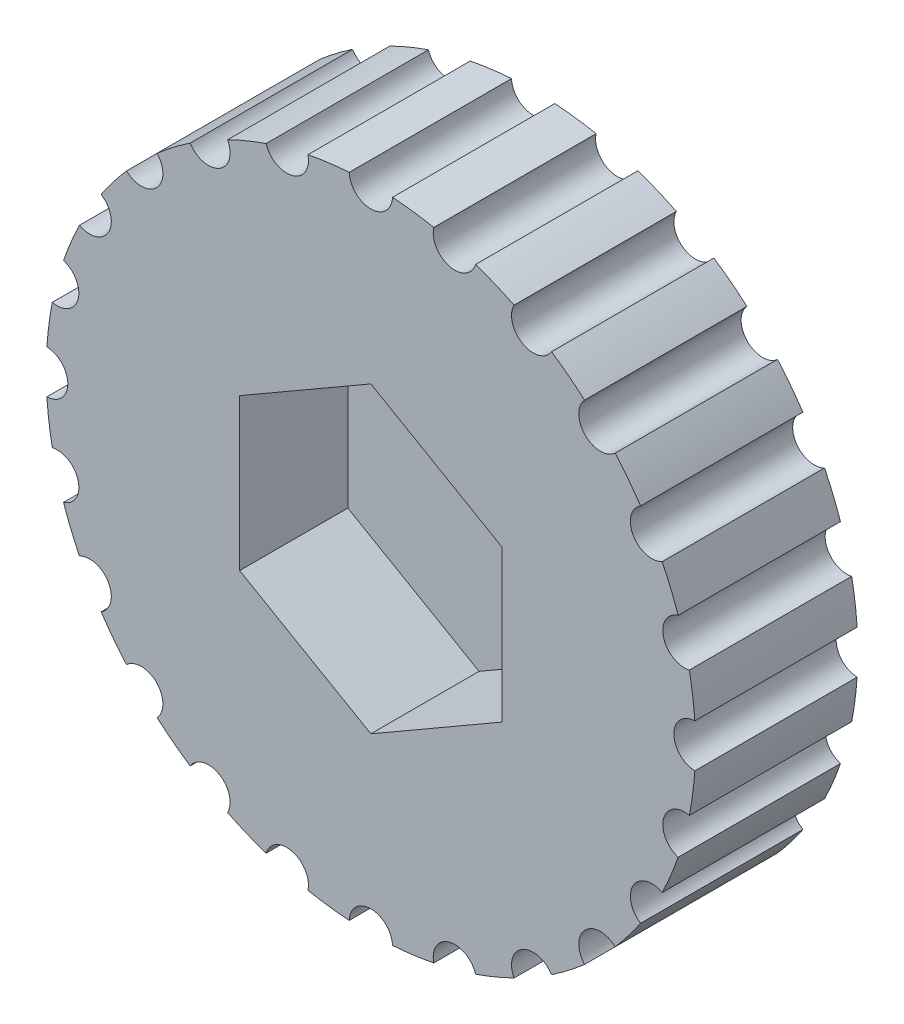
SolidWorks part; units mm, degrees
ref_plane "Front" through (0, 0, 0) normal (0, 0, 1) x (1, 0, 0)
ref_plane "Top" through (0, 0, 0) normal (0, 1, 0) x (1, 0, 0)
ref_plane "Right" through (0, 0, 0) normal (1, 0, 0) x (0, 0, -1)
sketch "Sketch1" plane through (0, 0, 0) normal (0, 0, 1) x (1, 0, 0)
  circle A0 centre (0, 0) radius 30
extrude "Boss-Extrude1" add sketch "Sketch1" along normal blind 15
sketch "Sketch2" plane through (0, 0, 15) normal (0, 0, 1) x (1, 0, 0)
  line L1 (0, 14) -> (-12.1244, 7)
  line L2 (-12.1244, 7) -> (-12.1244, -7)
  line L3 (-12.1244, -7) -> (0, -14)
  line L4 (0, -14) -> (12.1244, -7)
  line L5 (12.1244, -7) -> (12.1244, 7)
  line L6 (12.1244, 7) -> (0, 14)
  circle A0 centre (0, 0) radius 14 construction
  circle A1 centre (0, 0) radius 12.1244 construction
extrude "Cut-Extrude1" cut sketch "Sketch2" against normal blind 10
sketch "Sketch3" plane through (0, 0, 0) normal (0, 0, -1) x (-1, 0, 0)
  line L0 (0, 0) -> (0, 39.3885) construction
  circle A31 centre (0, 30) radius 2
  circle A32 centre (0, 0) radius 30 construction
  circle A33 centre (7.7646, 28.9778) radius 2
  circle A34 centre (15, 25.9808) radius 2
  circle A35 centre (21.2132, 21.2132) radius 2
  circle A36 centre (25.9808, 15) radius 2
  circle A37 centre (28.9778, 7.7646) radius 2
  circle A38 centre (30, 0) radius 2
  circle A39 centre (28.9778, -7.7646) radius 2
  circle A40 centre (25.9808, -15) radius 2
  circle A41 centre (21.2132, -21.2132) radius 2
  circle A42 centre (15, -25.9808) radius 2
  circle A43 centre (7.7646, -28.9778) radius 2
  circle A44 centre (0, -30) radius 2
  circle A45 centre (-7.7646, -28.9778) radius 2
  circle A46 centre (-15, -25.9808) radius 2
  circle A47 centre (-21.2132, -21.2132) radius 2
  circle A48 centre (-25.9808, -15) radius 2
  circle A49 centre (-28.9778, -7.7646) radius 2
  circle A50 centre (-30, 0) radius 2
  circle A51 centre (-28.9778, 7.7646) radius 2
  circle A52 centre (-25.9808, 15) radius 2
  circle A53 centre (-21.2132, 21.2132) radius 2
  circle A54 centre (-15, 25.9808) radius 2
  circle A55 centre (-7.7646, 28.9778) radius 2
  point P55 (0, 0)
  dimension "D1" = 24
extrude "Cut-Extrude2" cut sketch "Sketch3" against normal through all
sketch "Sketch4" plane through (0, 0, 0) normal (0, 0, -1) x (-1, 0, 0)
  circle A0 centre (0, 0) radius 10
